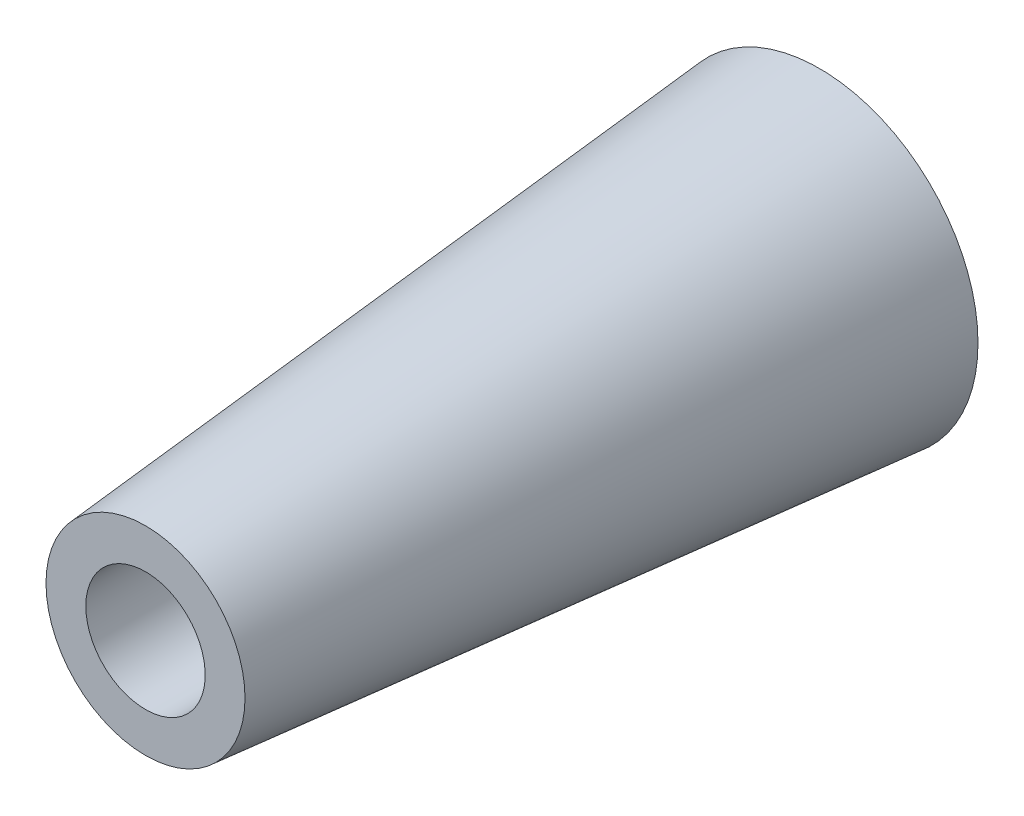
SolidWorks part; units mm, degrees
material "ABS"
ref_plane "Front Plane" through (0, 0, 0) normal (0, 0, 1) x (1, 0, 0)
ref_plane "Top Plane" through (0, 0, 0) normal (0, 1, 0) x (1, 0, 0)
ref_plane "Right Plane" through (0, 0, 0) normal (1, 0, 0) x (0, 0, -1)
sketch "Sketch1" plane through (0, 0, 0) normal (0, 0, 1) x (1, 0, 0)
  circle A0 centre (0, 0) radius 7.5
  dimension "D1" = 15
extrude "Boss-Extrude" add sketch "Sketch1" along normal blind 50.8
draft "Draft3" type of draft neutral plane draft angle 5 faces to draft 1 face at (7.5, 0, 50.8) neutral plane through (0, 0, 50.8) neutral plane normal (0, 0, 1) parameters "D1"=5
sketch "Sketch2" plane through (0, 0, 0) normal (0, 0, -1) x (-1, 0, 0)
  circle A0 centre (0, 0) radius 4.5
  dimension "D1" = 9
extrude "Cut-Extrude1" cut sketch "Sketch2" against normal through all
